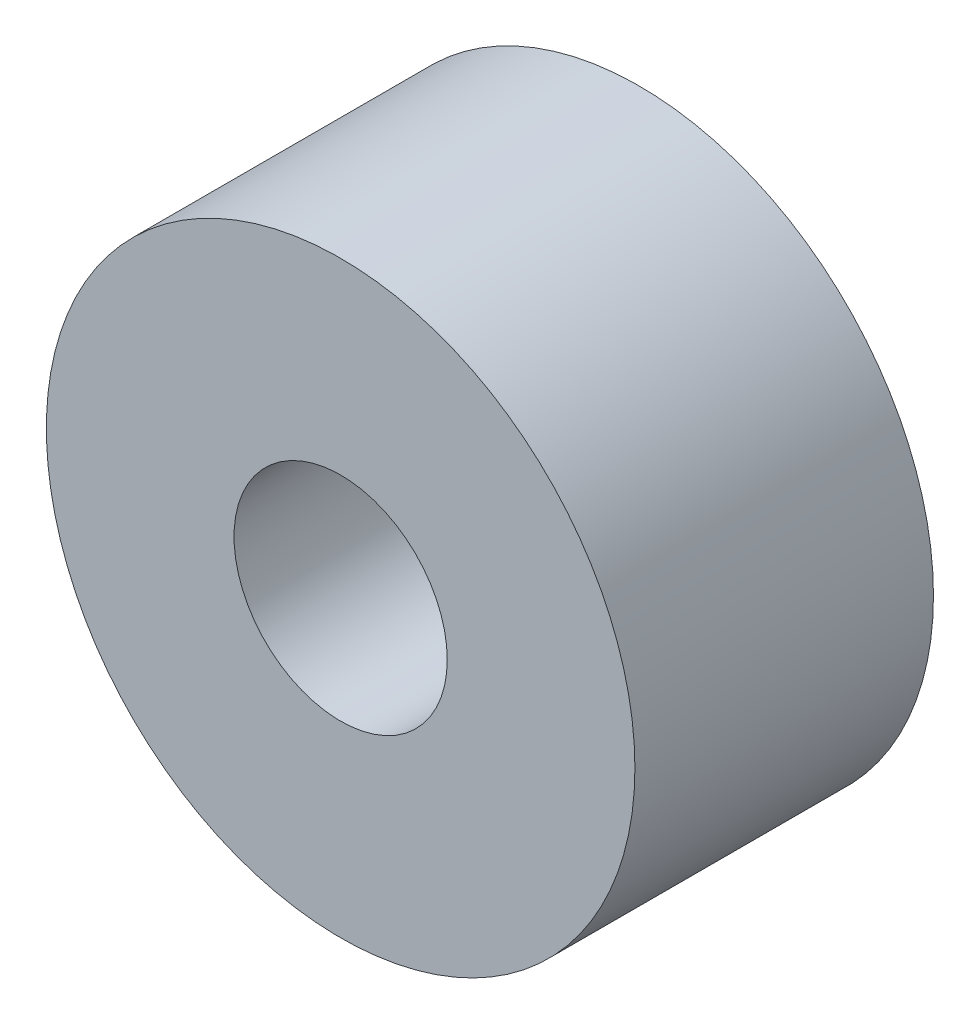
SolidWorks part; units mm, degrees
material "Alloy Steel"
ref_plane "Front Plane" through (0, 0, 0) normal (0, 0, 1) x (1, 0, 0)
ref_plane "Top Plane" through (0, 0, 0) normal (0, 1, 0) x (1, 0, 0)
ref_plane "Right Plane" through (0, 0, 0) normal (1, 0, 0) x (0, 0, -1)
sketch "Sketch1" plane through (0, 0, 0) normal (0, 0, 1) x (1, 0, 0)
  circle A9 centre (0, 0) radius 17.526
  circle A10 centre (0, 0) radius 6.35
  dimension "D1" = 35.052
  dimension "D2" = 12.7
extrude "Boss-Extrude1" add sketch "Sketch1" along normal blind 17.78
